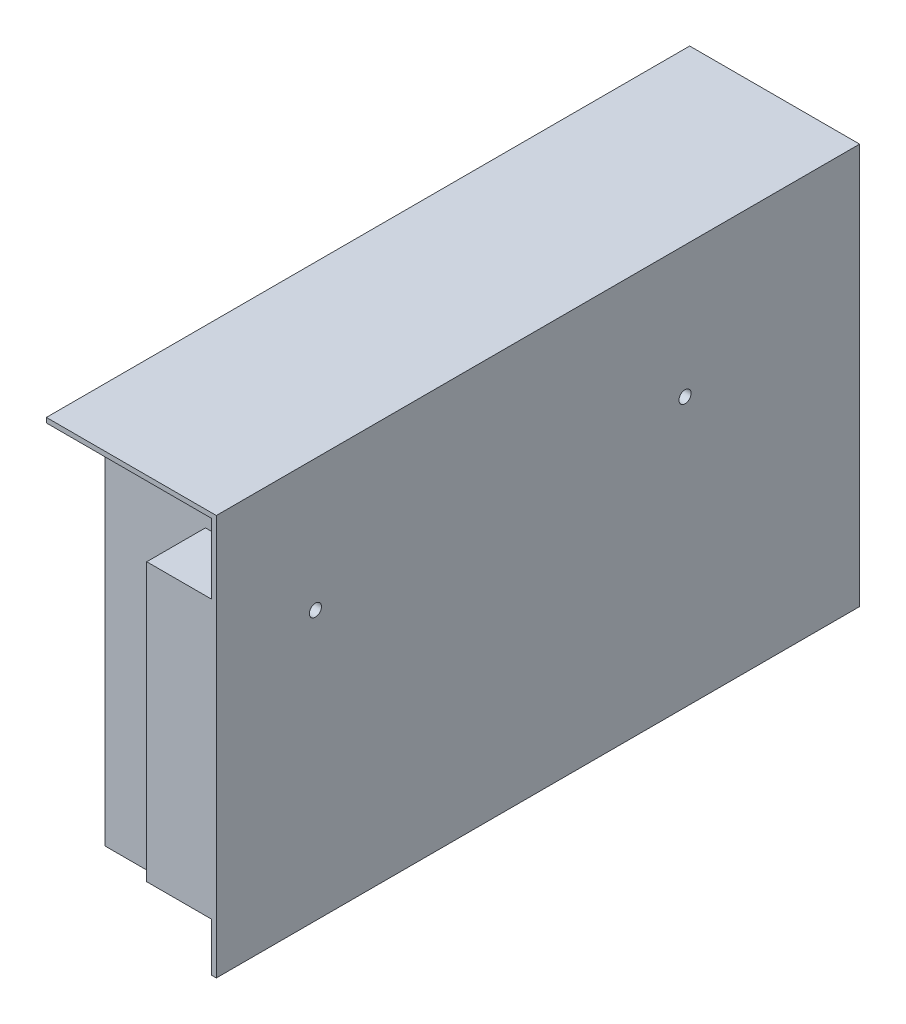
SolidWorks part; units mm, degrees
ref_plane "Front Plane" through (0, 0, 0) normal (0, 0, 1) x (1, 0, 0)
ref_plane "Top Plane" through (0, 0, 0) normal (0, 1, 0) x (1, 0, 0)
ref_plane "Right Plane" through (0, 0, 0) normal (1, 0, 0) x (0, 0, -1)
sketch "Sketch1" plane through (0, 0, 0) normal (1, 0, 0) x (0, 0, -1)
  line L1 (-56.8425, 19.7955) -> (102.1575, 19.7955)
  line L2 (-56.8425, 19.7955) -> (-56.8425, -79.2045)
  line L3 (-56.8425, -79.2045) -> (102.1575, -79.2045)
  line L4 (102.1575, 19.7955) -> (102.1575, -79.2045)
  dimension "D1" = 159
  dimension "D2" = 99
extrude "Boss-Extrude1" add sketch "Sketch1" along normal blind 42
sketch "Sketch2" plane through (0, 0, 0) normal (-1, 0, 0) x (0, 0, 1)
  line L0 (56.8425, 18.5955) -> (42.3425, 18.5955)
  line L1 (56.8425, 19.7955) -> (56.8425, -79.2045) construction
  line L2 (42.3425, 18.5955) -> (42.3425, -79.2045)
  line L3 (42.3425, -79.2045) -> (56.8425, -79.2045)
  line L4 (56.8425, -79.2045) -> (56.8425, 18.5955)
  line L5 (56.8425, -79.2045) -> (-102.1575, -79.2045) construction
  line L6 (-102.1575, 19.7955) -> (56.8425, 19.7955) construction
  dimension "D1" = 1.2
  dimension "D2" = 14.5
extrude "Cut-Extrude1" cut sketch "Sketch2" against normal offset from surface (40.8 mm away) 1.2 up to face at (42, -29.7045, -22.6575)
sketch "Sketch3" plane through (40.8, 0, 0) normal (-1, 0, 0) x (0, 0, 1)
  line L0 (42.3425, 18.5955) -> (42.3425, -79.2045) construction
  line L1 (42.3425, 1.2955) -> (56.8425, 1.2955)
  line L2 (42.3425, 1.2955) -> (42.3425, -67.2045)
  line L3 (42.3425, -67.2045) -> (56.8425, -67.2045)
  line L4 (56.8425, 1.2955) -> (56.8425, -67.2045)
  line L5 (56.8425, -79.2045) -> (56.8425, 18.5955) construction
  line L6 (42.3425, -79.2045) -> (56.8425, -79.2045) construction
  dimension "D1" = 12
  dimension "D2" = 68.5
extrude "Boss-Extrude2" add sketch "Sketch3" along normal blind 16
sketch "Sketch5" plane through (42, 0, 0) normal (1, 0, 0) x (0, 0, -1)
  line L0 (102.1575, 19.7955) -> (-56.8425, 19.7955) construction
  line L1 (-56.8425, 19.7955) -> (-56.8425, -79.2045) construction
  circle A0 centre (-32.3425, -12.7045) radius 1.5
  circle A1 centre (59.0095, -12.7045) radius 1.5
  point P4 (-32.3425, -11.2045)
  point P7 (-33.8425, -12.7045)
  dimension "D1" = 3
  dimension "D2" = 31
  dimension "D3" = 23
extrude "Cut-Extrude2" cut sketch "Sketch5" against normal blind 5
